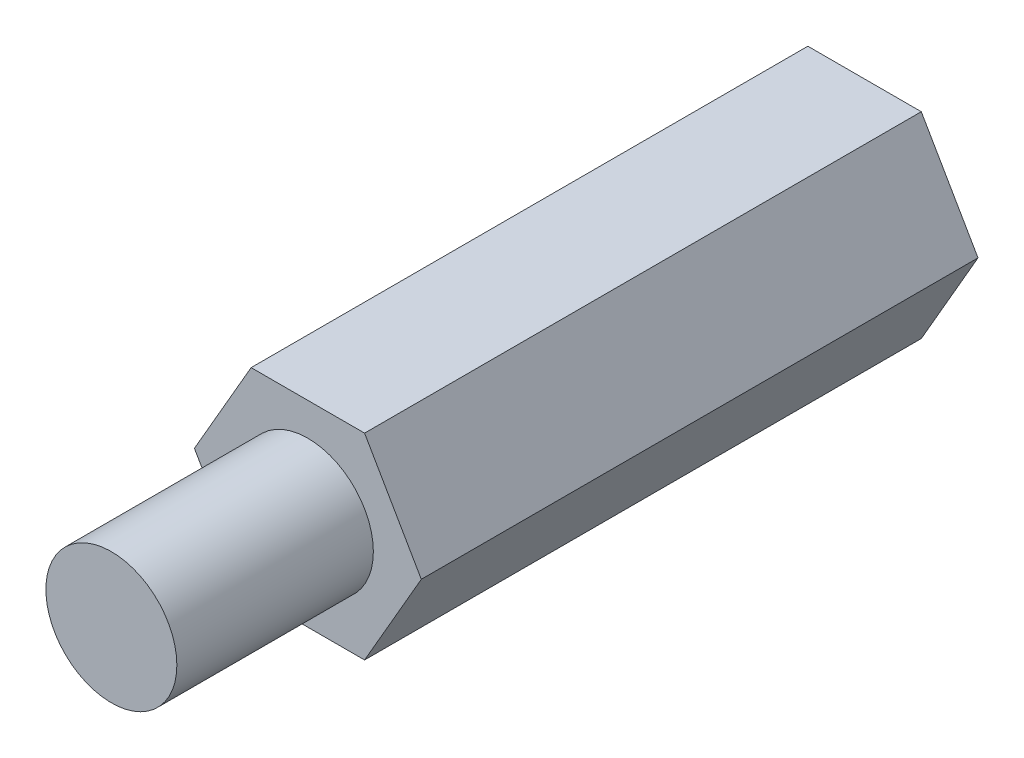
SolidWorks part; units mm, degrees
ref_plane "Front Plane" through (0, 0, 0) normal (0, 0, 1) x (1, 0, 0)
ref_plane "Top Plane" through (0, 0, 0) normal (0, 1, 0) x (1, 0, 0)
ref_plane "Right Plane" through (0, 0, 0) normal (1, 0, 0) x (0, 0, -1)
sketch "Sketch1" plane through (0, 0, 0) normal (0, 0, 1) x (1, 0, 0)
  line L1 (1.7321, 3) -> (-1.7321, 3)
  line L2 (-1.7321, 3) -> (-3.4641, 0)
  line L3 (-3.4641, 0) -> (-1.7321, -3)
  line L4 (-1.7321, -3) -> (1.7321, -3)
  line L5 (1.7321, -3) -> (3.4641, 0)
  line L6 (3.4641, 0) -> (1.7321, 3)
  circle A0 centre (0, 0) radius 3 construction
  dimension "D1" = 6
extrude "Boss-Extrude1" add sketch "Sketch1" along normal blind 17
sketch "Sketch2" plane through (0, 0, 17) normal (0, 0, 1) x (1, 0, 0)
  circle A0 centre (0, 0) radius 2
  dimension "D1" = 4
extrude "Boss-Extrude2" add sketch "Sketch2" along normal blind 6
hole_wizard "Ø3.0mm Dowel Hole1" positions "Sketch4" profile "Sketch5" hole size "Ø3.0" standard "ANSI Metric"
sketch "Sketch4" plane through (0, 0, 0) normal (0, 0, -1) x (-1, 0, 0)
  point P0 (0, 0)
sketch "Sketch5" plane through (0, 0, 0) normal (1, 0, 0) x (0, 1, 0)
  line L0 (0, 0) -> (0, 6.9013)
  line L1 (0, 6.9013) -> (1.5, 6)
  line L2 (1.5, 6) -> (1.5, 0)
  line L5 (1.5, 0) -> (0, 0)
  line L10 (0, 6.9013) -> (-1.5, 6) construction
  line L11 (0, -6.35) -> (0, 107.95) construction
  dimension "Hole Dia." = 3
  dimension "Hole Depth" = 6
  dimension "Drill Angle" = 118
